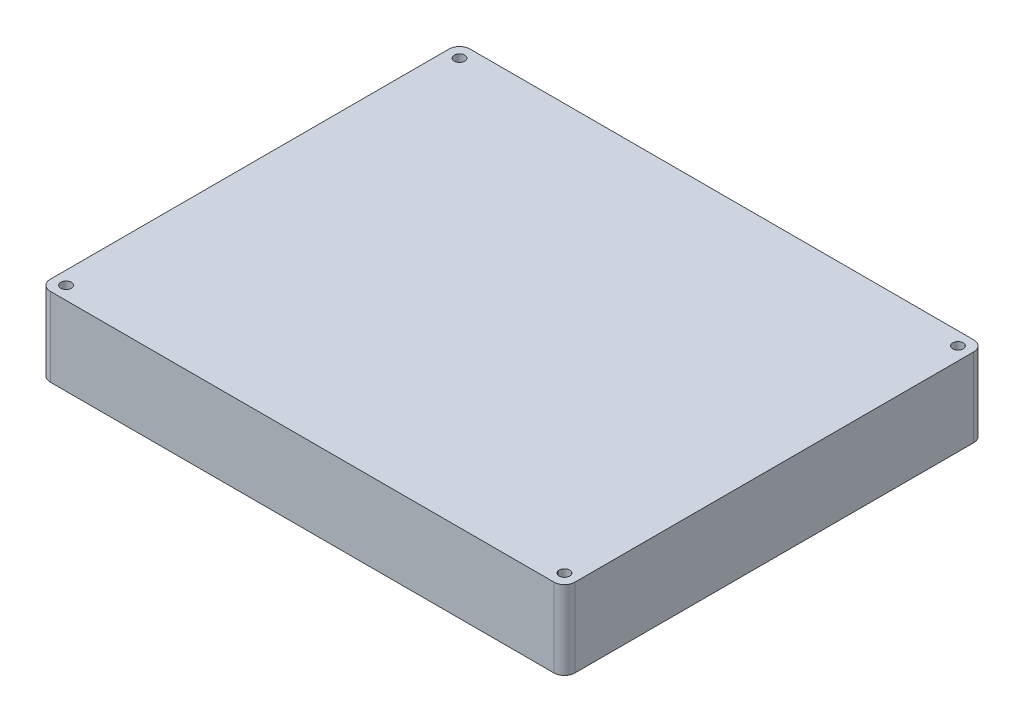
SolidWorks part; units mm, degrees
ref_plane "前视基准面" through (0, 0, 0) normal (0, 0, 1) x (1, 0, 0)
ref_plane "上视基准面" through (0, 0, 0) normal (0, 1, 0) x (1, 0, 0)
ref_plane "右视基准面" through (0, 0, 0) normal (1, 0, 0) x (0, 0, -1)
sketch "草图1" plane through (0, 0, 0) normal (0, 1, 0) x (1, 0, 0)
  line L1 (48, -40) -> (-48, -40)
  line L2 (50, -38) -> (50, 38)
  line L3 (48, 40) -> (-48, 40)
  line L4 (-50, -38) -> (-50, 38)
  line L5 (50, -40) -> (-50, 40) construction
  line L6 (50, 40) -> (-50, -40) construction
  arc A0 (-48, -40) -> (-50, -38) centre (-48, -38) cw
  arc A1 (-48, 40) -> (-50, 38) centre (-48, 38) ccw
  arc A2 (50, 38) -> (48, 40) centre (48, 38) ccw
  arc A3 (48, -40) -> (50, -38) centre (48, -38) ccw
  point P0 (0, 0)
  dimension "D3" = 2
  dimension "D1" = 100
  dimension "D2" = 80
extrude "凸台-拉伸1" add sketch "草图1" along normal blind 15
sketch "草图2" plane through (0, 15, 0) normal (0, 1, 0) x (1, 0, 0)
  line L0 (-47.5, 37.5) -> (47.5, 37.5) construction
  line L1 (47.5, 37.5) -> (47.5, -37.5) construction
  line L2 (47.5, -37.5) -> (-47.5, -37.5) construction
  line L3 (-47.5, -37.5) -> (-47.5, 37.5) construction
  line L4 (-50, 38) -> (-50, -38) construction
  line L5 (48, 40) -> (-48, 40) construction
  line L6 (50, -38) -> (50, 38) construction
  line L7 (-48, -40) -> (48, -40) construction
  circle A0 centre (-47.5, 37.5) radius 1
  circle A1 centre (47.5, 37.5) radius 1
  circle A2 centre (47.5, -37.5) radius 1
  circle A4 centre (-47.5, -37.5) radius 1
  dimension "D1" = 2
  dimension "D2" = 2
  dimension "D3" = 2
  dimension "D4" = 2
  dimension "D5" = 2.5
  dimension "D6" = 2.5
  dimension "D7" = 2.5
  dimension "D8" = 2.5
extrude "切除-拉伸1" cut sketch "草图2" against normal through all
